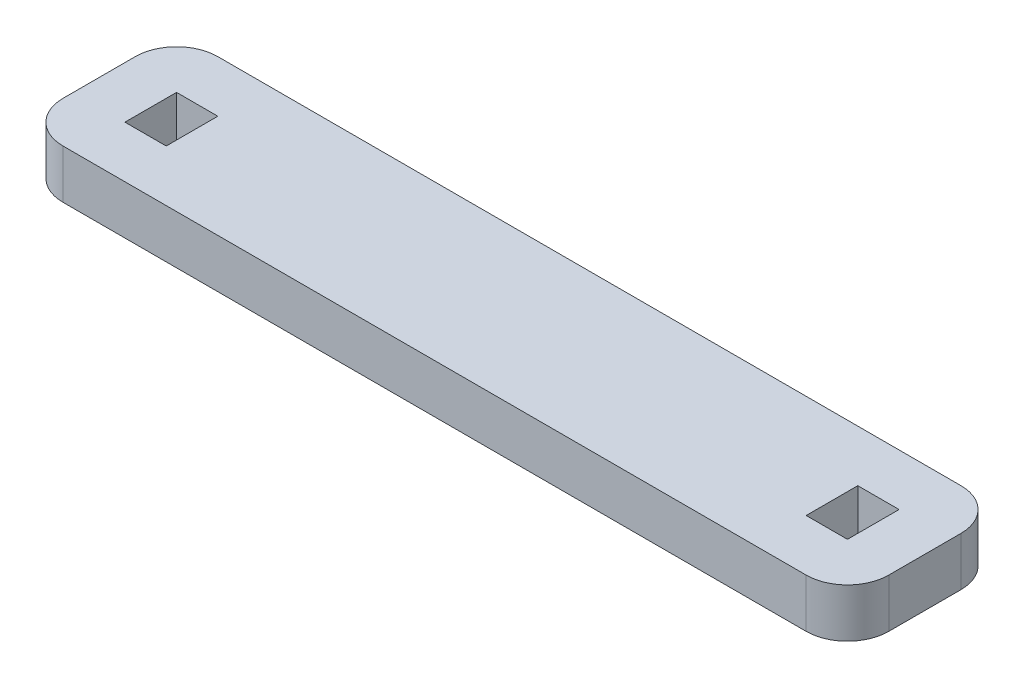
SolidWorks part; units mm, degrees
ref_plane "Front Plane" through (0, 0, 0) normal (0, 0, 1) x (1, 0, 0)
ref_plane "Top Plane" through (0, 0, 0) normal (0, 1, 0) x (1, 0, 0)
ref_plane "Right Plane" through (0, 0, 0) normal (1, 0, 0) x (0, 0, -1)
sketch "Sketch1" plane through (0, 0, 0) normal (0, 1, 0) x (1, 0, 0)
  line L0 (-20.955, 0) -> (20.955, 0) construction
  line L6 (25.4, -4.7625) -> (-25.4, -4.7625)
  line L7 (-19.685, -1.5875) -> (-22.225, -1.5875)
  line L8 (-19.685, -1.5875) -> (-19.685, 1.5875)
  line L9 (-19.685, 1.5875) -> (-22.225, 1.5875)
  line L10 (-22.225, -1.5875) -> (-22.225, 1.5875)
  line L11 (-19.685, -1.5875) -> (-22.225, 1.5875) construction
  line L12 (-19.685, 1.5875) -> (-22.225, -1.5875) construction
  line L13 (22.225, -1.5875) -> (19.685, -1.5875)
  line L14 (22.225, -1.5875) -> (22.225, 1.5875)
  line L15 (22.225, 1.5875) -> (19.685, 1.5875)
  line L16 (19.685, -1.5875) -> (19.685, 1.5875)
  line L17 (22.225, -1.5875) -> (19.685, 1.5875) construction
  line L18 (22.225, 1.5875) -> (19.685, -1.5875) construction
  line L19 (25.4, -4.7625) -> (25.4, 4.7625)
  line L20 (25.4, 4.7625) -> (-25.4, 4.7625)
  line L21 (-25.4, -4.7625) -> (-25.4, 4.7625)
  line L22 (25.4, -4.7625) -> (-25.4, 4.7625) construction
  line L23 (25.4, 4.7625) -> (-25.4, -4.7625) construction
  point P0 (0, 0)
  point P1 (0, 0)
  point P6 (-20.955, 0)
  point P11 (20.955, 0)
  dimension "D1" = 9.525
  dimension "D2" = 3.175
  dimension "D3" = 2.54
  dimension "D4" = 41.91
  dimension "D5" = 3.175
extrude "Boss-Extrude1" add sketch "Sketch1" along normal mid plane 3
fillet "Fillet1" radius 2.54 4 edges at (-25.4, 0, -4.7625) (25.4, 0, -4.7625) (25.4, 0, 4.7625) (-25.4, 0, 4.7625)
